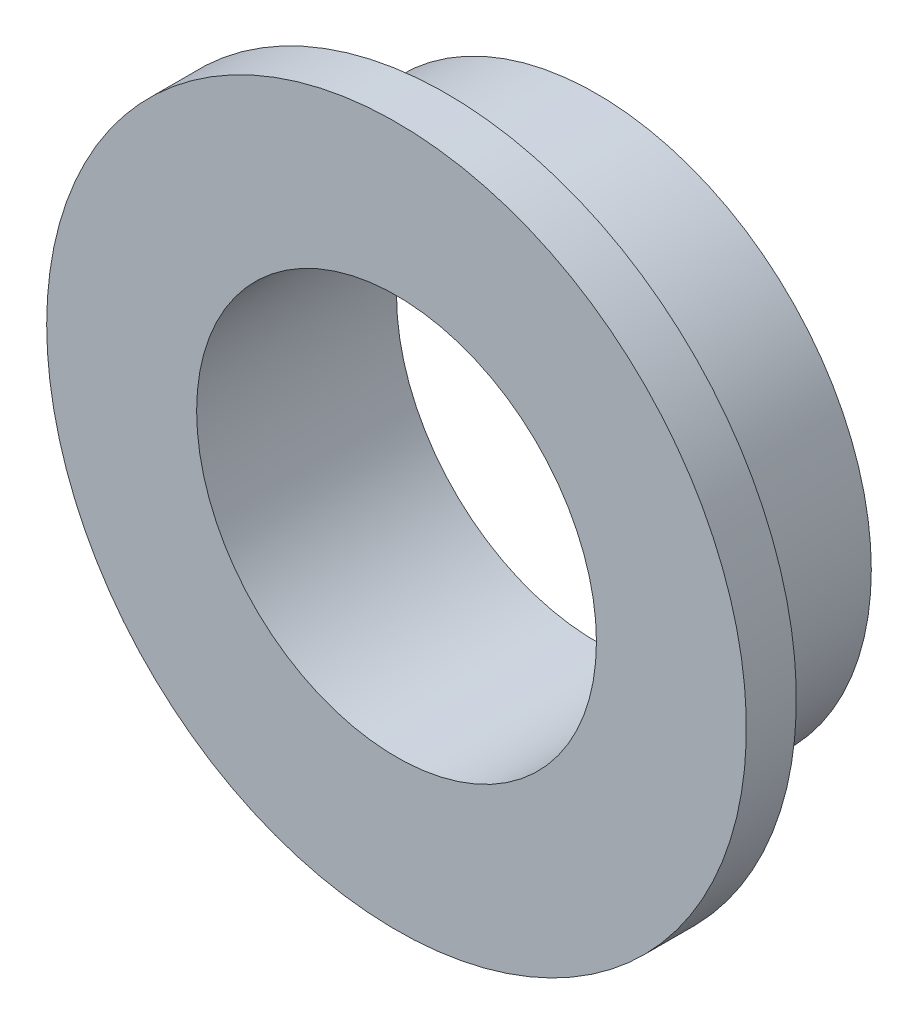
SolidWorks part; units mm, degrees
material "AISI Type 316L stainless steel"
ref_plane "Front Plane" through (0, 0, 0) normal (0, 0, 1) x (1, 0, 0)
ref_plane "Top Plane" through (0, 0, 0) normal (0, 1, 0) x (1, 0, 0)
ref_plane "Right Plane" through (0, 0, 0) normal (1, 0, 0) x (0, 0, -1)
sketch "Sketch1" plane through (0, 0, 0) normal (1, 0, 0) x (0, 0, -1)
  line L0 (0, 0) -> (-38.7755, 0) construction
  line L1 (0, 4) -> (-4, 4)
  line L2 (-4, 4) -> (-4, 7)
  line L3 (-4, 7) -> (-3, 7)
  line L4 (-3, 7) -> (-3, 5.5)
  line L5 (-3, 5.5) -> (0, 5.5)
  line L6 (0, 5.5) -> (0, 4)
  dimension "D1" = 8
  dimension "D2" = 11
  dimension "D3" = 1
  dimension "D4" = 14
  dimension "D5" = 4
revolve "Revolve1" add sketch "Sketch1" angle 360 about L0
